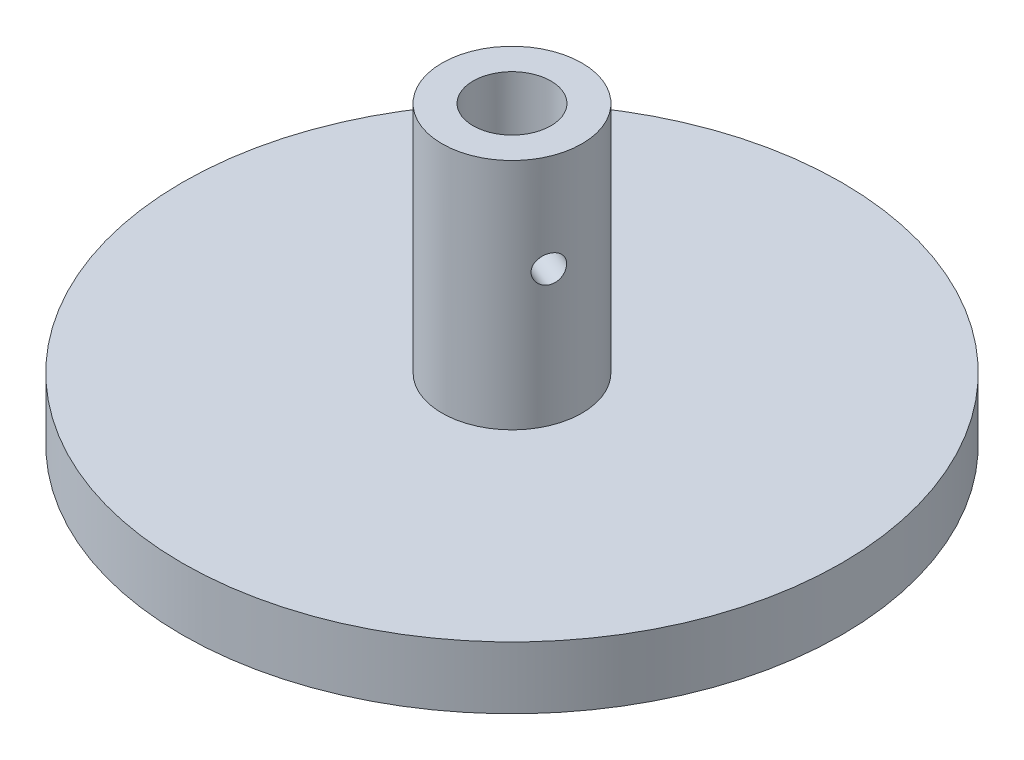
SolidWorks part; units mm, degrees
ref_plane "Alzado" through (0, 0, 0) normal (0, 0, 1) x (1, 0, 0)
ref_plane "Planta" through (0, 0, 0) normal (0, 1, 0) x (1, 0, 0)
ref_plane "Vista lateral" through (0, 0, 0) normal (1, 0, 0) x (0, 0, -1)
sketch "Croquis1" plane through (0, 0, 0) normal (0, 1, 0) x (1, 0, 0)
  circle A0 centre (-10.4544, 0) radius 2.5
  circle A1 centre (-10.4544, 0) radius 4.5
extrude "Saliente-Extruir1" add sketch "Croquis1" along normal blind 15
sketch "Croquis2" plane through (0, 0, 0) normal (0, -1, 0) x (1, 0, 0)
  circle A0 centre (-10.4544, 0) radius 21.2
extrude "Saliente-Extruir2" add sketch "Croquis2" along normal blind 4
sketch "Croquis4" plane through (0, -4, 0) normal (0, -1, 0) x (1, 0, 0)
  circle A1 centre (-10.4544, 0) radius 2.5
extrude "Cortar-Extruir1" cut sketch "Croquis4" against normal blind 4
hole_wizard "Taladro roscado M2.2x0.451" positions "Croquis3D1" profile "Croquis5" tap size "M2.2x0.45" standard "Ansi Metric"
sketch3d "Croquis3D1"
  point P1 (-14.6058, 8.7208, -1.7367)
sketch "Croquis5" plane through (-14.6058, 8.7208, -1.7367) normal (0, 1, 0) x (-0.3859, 0, 0.9225)
  line L0 (0, 0) -> (0, 32.0258)
  line L1 (0, 32.0258) -> (0.875, 31.5)
  line L2 (0.875, 31.5) -> (0.875, 0)
  line L5 (0.875, 0) -> (0, 0)
  line L10 (0, 32.0258) -> (-0.875, 31.5) construction
  line L11 (0, -6.35) -> (0, 107.95) construction
  dimension "Diámetro de perforador para roscar" = 1.75
  dimension "Profundidad de perforador para roscar" = 31.5
  dimension "Ángulo de perforador" = 118
cosmetic thread "Rosca de taladro1" parameters "D1"=4.4, "D2"=2.2
